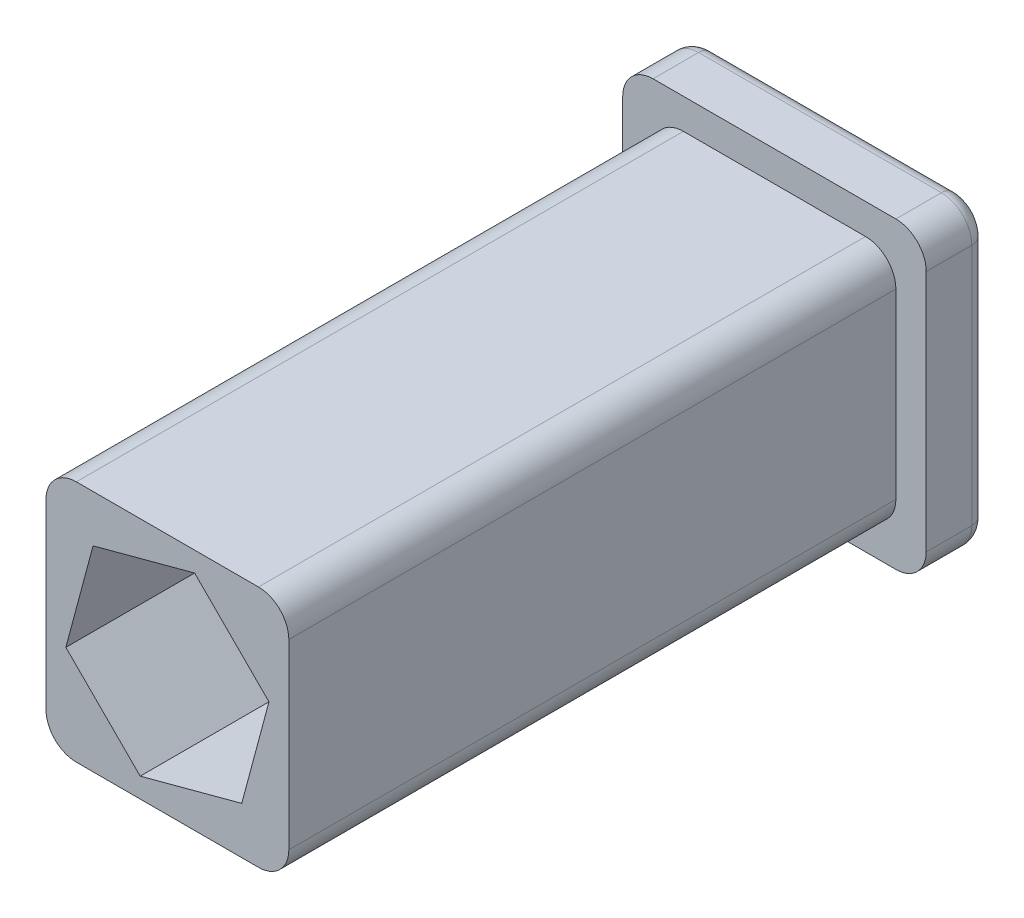
SolidWorks part; units mm, degrees
ref_plane "Front Plane" through (0, 0, 0) normal (0, 0, 1) x (1, 0, 0)
ref_plane "Top Plane" through (0, 0, 0) normal (0, 1, 0) x (1, 0, 0)
ref_plane "Right Plane" through (0, 0, 0) normal (1, 0, 0) x (0, 0, -1)
sketch "Sketch1" plane through (0, 0, 0) normal (0, 0, 1) x (1, 0, 0)
  line L0 (-4.0826, -3.6009) -> (-14.0826, 6.3991) construction
  line L1 (-14.0826, 6.3991) -> (-4.0826, 6.3991)
  line L2 (-14.0826, 6.3991) -> (-14.0826, -3.6009)
  line L3 (-14.0826, -3.6009) -> (-4.0826, -3.6009)
  line L4 (-4.0826, 6.3991) -> (-4.0826, -3.6009)
  dimension "D1" = 10
  dimension "D2" = 10
extrude "Boss-Extrude1" add sketch "Sketch1" along normal blind 2
fillet "Fillet2" radius 1 3 edges at (-4.0826, 6.3991, 1) (-14.0826, 6.3991, 1) (-14.0826, -3.6009, 1)
fillet "Fillet3" radius 1 1 edges at (-4.0826, -3.6009, 1)
fillet "Fillet5" radius 0.5 8 edges at (-4.3755, 6.1062, 0) (-9.0826, 6.3991, 0) (-13.7897, 6.1062, 0) (-14.0826, 1.3991, 0) (-13.7897, -3.308, 0) (-9.0826, -3.6009, 0) (-4.3755, -3.308, 0) (-4.0826, 1.3991, 0)
sketch "Sketch6" plane through (0, 0, 2) normal (0, 0, 1) x (1, 0, 0)
  line L0 (-4.0826, -3.6009) -> (-14.0826, 6.3991) construction
  line L1 (-13.0826, 5.3991) -> (-5.0826, 5.3991)
  line L2 (-13.0826, 5.3991) -> (-13.0826, -2.6009)
  line L3 (-13.0826, -2.6009) -> (-5.0826, -2.6009)
  line L4 (-5.0826, 5.3991) -> (-5.0826, -2.6009)
  line L5 (-14.0826, 6.3991) -> (-4.0826, 6.3991) construction
  line L6 (-14.0826, -3.6009) -> (-4.0826, -3.6009) construction
  dimension "D1" = 1
  dimension "D2" = 1
extrude "Boss-Extrude2" add sketch "Sketch6" along normal blind 20
fillet "Fillet7" radius 1 4 edges at (-13.0826, -2.6009, 12) (-5.0826, -2.6009, 12) (-5.0826, 5.3991, 12) (-13.0826, 5.3991, 12)
hole_wizard "M3 Clearance Hole1" positions "Sketch4" profile "Sketch5" hole size "M3" standard "ISO" end condition through all
sketch "Sketch4" plane through (0, 0, 0) normal (0, 0, -1) x (-1, 0, 0)
  line L0 (4.0826, -3.6009) -> (14.0826, 6.3991) construction
  point P0 (9.0826, 1.3991)
sketch "Sketch5" plane through (-9.0826, 1.3991, 0) normal (1, 0, 0) x (0, 1, 0)
  line L0 (0, 0) -> (0, 22)
  line L1 (0, 22) -> (1.7, 22)
  line L2 (1.7, 22) -> (1.7, 0)
  line L5 (1.7, 0) -> (0, 0)
  line L11 (0, -6.35) -> (0, 107.95) construction
  dimension "Thru Hole Dia." = 3.4
  dimension "Thru Hole Depth" = 22
sketch "Sketch7" plane through (0, 0, 22) normal (0, 0, 1) x (1, 0, 0)
  line L0 (-4.0826, -3.6009) -> (-14.0826, 6.3991) construction
  line L1 (-6.6331, -1.0504) -> (-5.7365, 2.2957)
  line L2 (-5.7365, 2.2957) -> (-8.186, 4.7451)
  line L3 (-8.186, 4.7451) -> (-11.5321, 3.8486)
  line L4 (-11.5321, 3.8486) -> (-12.4286, 0.5025)
  line L5 (-12.4286, 0.5025) -> (-9.9791, -1.947)
  line L6 (-9.9791, -1.947) -> (-6.6331, -1.0504)
  circle A0 centre (-9.0826, 1.3991) radius 3 construction
  dimension "D1" = 6
extrude "Cut-Extrude1" cut sketch "Sketch7" against normal blind 20
